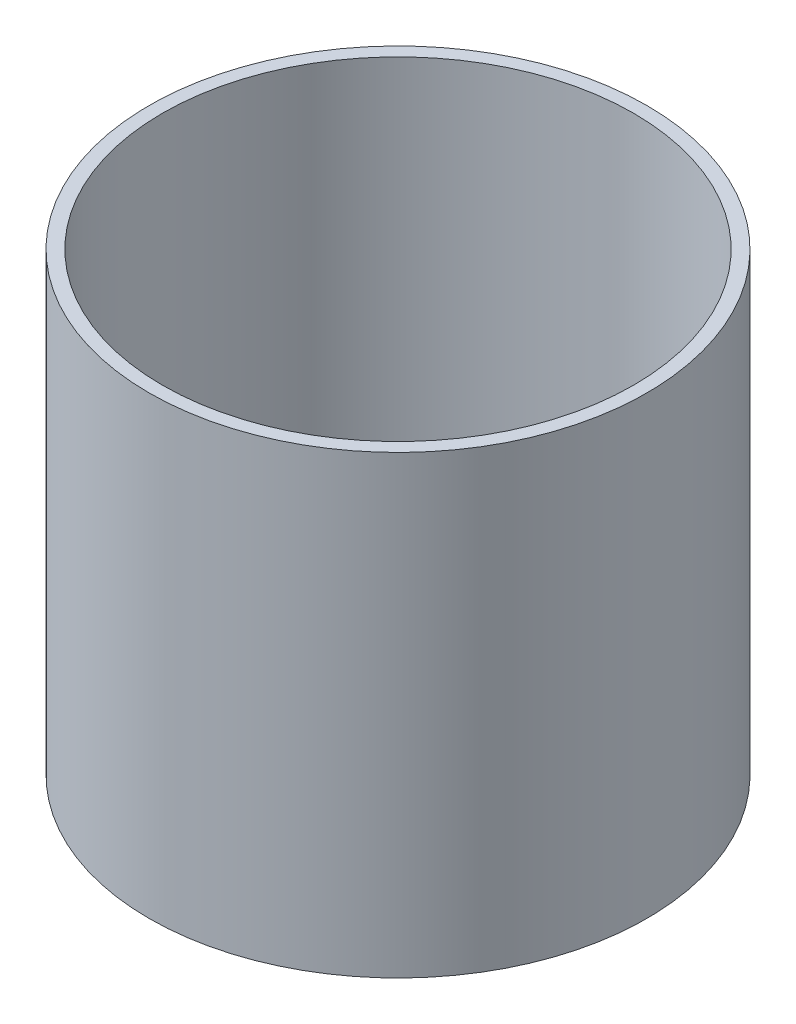
SolidWorks part; units mm, degrees
material "Thornel Mat VMA"
ref_plane "Alzado" through (0, 0, 0) normal (0, 0, 1) x (1, 0, 0)
ref_plane "Planta" through (0, 0, 0) normal (0, 1, 0) x (1, 0, 0)
ref_plane "Vista lateral" through (0, 0, 0) normal (1, 0, 0) x (0, 0, -1)
sketch "Croquis1" plane through (0, 0, 0) normal (0, 1, 0) x (1, 0, 0)
  circle A0 centre (0, 0) radius 70
  dimension "D1" = 140
extrude "Extruir-Lámina1" add sketch "Croquis1" along normal blind 128 thin thin type one direction reverse wall 3.75
